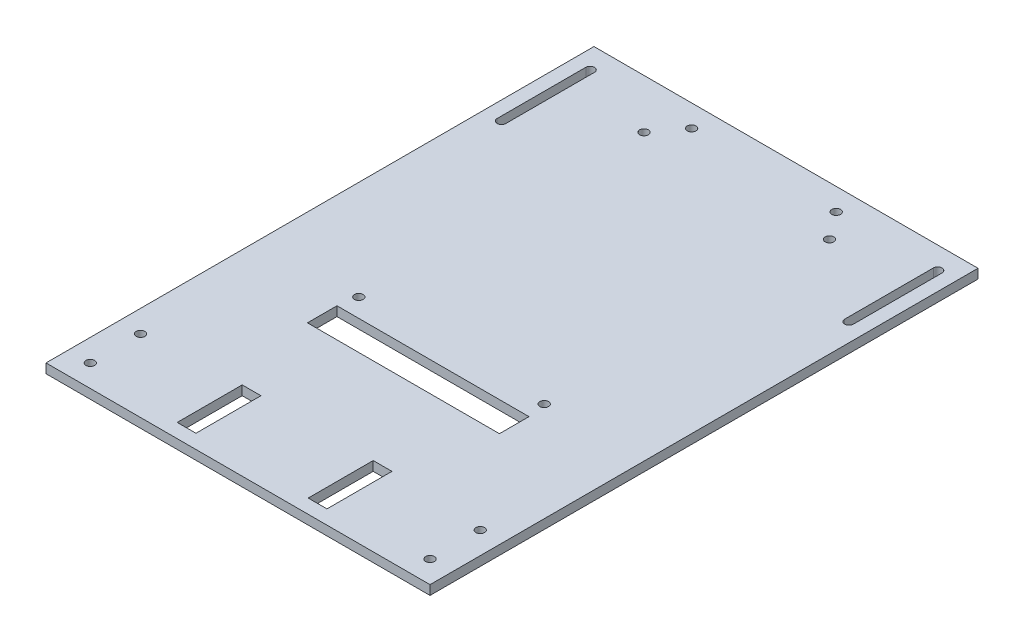
SolidWorks part; units mm, degrees
ref_plane "Front Plane" through (0, 0, 0) normal (0, 0, 1) x (1, 0, 0)
ref_plane "Top Plane" through (0, 0, 0) normal (0, 1, 0) x (1, 0, 0)
ref_plane "Right Plane" through (0, 0, 0) normal (1, 0, 0) x (0, 0, -1)
sketch "Sketch1" plane through (0, 0, 0) normal (0, 1, 0) x (1, 0, 0)
  line L1 (-65, -92.25) -> (65, -92.25)
  line L2 (-65, -92.25) -> (-65, 92.25)
  line L3 (-65, 92.25) -> (65, 92.25)
  line L4 (65, -92.25) -> (65, 92.25)
  line L5 (-65, -92.25) -> (65, 92.25) construction
  line L6 (-65, 92.25) -> (65, -92.25) construction
  point P0 (0, 0)
  dimension "D1" = 130
  dimension "D2" = 184.5
extrude "Boss-Extrude1" add sketch "Sketch1" along normal blind 3.175
sketch "Sketch4" plane through (0, 0, 0) normal (0, -1, 0) x (-1, 0, 0)
  line L6 (-58.825, 85.775) -> (-58.825, 55.775) construction
  line L7 (-57.35, 85.775) -> (-57.35, 55.775)
  line L8 (-60.3, 85.775) -> (-60.3, 55.775)
  line L36 (-65, -92.25) -> (-65, 92.25) construction
  line L46 (-65, 92.25) -> (65, 92.25) construction
  line L48 (58.825, 85.775) -> (58.825, 55.775) construction
  line L49 (60.3, 85.775) -> (60.3, 55.775)
  line L50 (57.35, 85.775) -> (57.35, 55.775)
  line L54 (65, 92.25) -> (65, -92.25) construction
  line L55 (65, -92.25) -> (-65, -92.25) construction
  arc A14 (-57.35, 85.775) -> (-60.3, 85.775) centre (-58.825, 85.775) ccw
  arc A15 (-60.3, 55.775) -> (-57.35, 55.775) centre (-58.825, 55.775) ccw
  circle A18 centre (-57.5, -84.75) radius 1.475
  circle A19 centre (-57.5, -67.75) radius 1.475
  arc A51 (60.3, 85.775) -> (57.35, 85.775) centre (58.825, 85.775) ccw
  arc A52 (57.35, 55.775) -> (60.3, 55.775) centre (58.825, 55.775) ccw
  circle A55 centre (57.5, -84.75) radius 1.475
  circle A56 centre (57.5, -67.75) radius 1.475
  point P2 (-58.825, 70.775)
  point P82 (58.825, 70.775)
  point P96 (-58.825, 87.25)
  point P100 (58.825, 87.25)
  dimension "D1" = 4.7
  dimension "D21" = 2.95
  dimension "D22" = 2.95
  dimension "D23" = 2.95
  dimension "D24" = 2.95
  dimension "D25" = 1.475
  dimension "D47" = 1.475
  dimension "D50" = 5
  dimension "D51" = 7.5
  dimension "D52" = 7.5
  dimension "D53" = 7.5
  dimension "D56" = 7.5
  dimension "D57" = 7.5
  dimension "D58" = 7.5
  dimension "D20" = 30
  dimension "D34" = 30
  dimension "D45" = 5
  dimension "D49" = 4.7
  dimension "D54" = 17
  dimension "D55" = 17
extrude "Cut-Extrude3" cut sketch "Sketch4" against normal through all
sketch "Sketch5" plane through (0, 0, 0) normal (0, -1, 0) x (1, 0, 0)
  line L0 (-23, -81.6775) -> (-23, -89.8725)
  line L1 (23, -91.5608) -> (23, -79.9892)
  line L3 (-28.3353, -87.25) -> (-20.6147, -87.25)
  line L4 (65, -92.25) -> (-65, -92.25) construction
  line L5 (65, -92.25) -> (-65, -92.25) construction
  circle A0 centre (-24.475, -85.775) radius 1.475
  circle A1 centre (24.475, -85.775) radius 1.475
  point P7 (-23.1414, -85.1449)
  point P10 (23, -85.775)
  point P16 (-24.475, -87.25)
  point P19 (-23, -85.775)
  point P21 (0, -92.25)
  dimension "D2" = 2.95
  dimension "D3" = 2.95
  dimension "D6" = 6.475
  dimension "D1" = 46
  dimension "D4" = 23
  dimension "D5" = 5
extrude "Cut-Extrude4" cut sketch "Sketch5" against normal blind 10 contours A0 | A1
sketch "Sketch6" plane through (0, 0, -92.25) normal (0, 0, -1) x (-1, 0, 0)
  line L1 (-65, 0) -> (65, 0)
  line L2 (-65, 0) -> (-65, 3.175)
  line L3 (-65, 3.175) -> (65, 3.175)
  line L4 (65, 0) -> (65, 3.175)
extrude "Boss-Extrude2" add sketch "Sketch6" along normal blind 1
sketch "Sketch7" plane through (0, 3.175, 0) normal (0, 1, 0) x (1, 0, 0)
  line L0 (-65, 93.25) -> (-65, -92.25) construction
  line L6 (-65, -92.25) -> (65, -92.25) construction
  line L7 (-25.35, -87.4884) -> (-19, -87.4884)
  line L8 (-25.35, -87.4884) -> (-25.35, -65.4884)
  line L9 (-25.35, -65.4884) -> (-19, -65.4884)
  line L10 (-19, -87.4884) -> (-19, -65.4884)
  line L11 (65, -92.25) -> (65, 93.25) construction
  line L12 (19, -87.4884) -> (25.35, -87.4884)
  line L13 (19, -87.4884) -> (19, -65.4884)
  line L14 (19, -65.4884) -> (25.35, -65.4884)
  line L15 (25.35, -87.4884) -> (25.35, -65.4884)
  dimension "D1" = 22
  dimension "D2" = 6.35
  dimension "D3" = 4.7616
  dimension "D4" = 39.65
  dimension "D5" = 6.35
  dimension "D6" = 22
  dimension "D7" = 4.7616
  dimension "D8" = 39.65
extrude "Cut-Extrude5" cut sketch "Sketch7" against normal through all both and the other way through all
sketch "Sketch8" plane through (0, 0, 0) normal (0, -1, 0) x (1, 0, 0)
  line L0 (-32.5, 92.25) -> (-32.5, 36.25)
  line L1 (-65, 92.25) -> (65, 92.25) construction
  line L3 (-32.5, 36.25) -> (32.5, 36.25)
  line L4 (-32.5, 36.25) -> (-32.5, 26.25)
  line L5 (-32.5, 26.25) -> (32.5, 26.25)
  line L6 (32.5, 36.25) -> (32.5, 26.25)
  line L7 (65, 92.25) -> (65, -93.25) construction
  dimension "D1" = 56
  dimension "D2" = 10
  dimension "D3" = 65
  dimension "D4" = 32.5
extrude "Cut-Extrude6" cut sketch "Sketch8" against normal blind 10 contours L6 L3 L4 L5
sketch "Sketch9" plane through (0, 0, 0) normal (0, -1, 0) x (-1, 0, 0)
  line L0 (-65, -92.25) -> (-65, 93.25) construction
  line L1 (30, 75.25) -> (-30, 75.25)
  line L2 (30, 75.25) -> (30, -12.75)
  line L3 (30, -12.75) -> (-30, -12.75)
  line L4 (-30, 75.25) -> (-30, -12.75)
  line L5 (30, 75.25) -> (-30, -12.75) construction
  line L6 (30, -12.75) -> (-30, 75.25) construction
  line L7 (-65, 93.25) -> (65, 93.25) construction
  circle A0 centre (30, -12.75) radius 1.475
  circle A1 centre (-30, -12.75) radius 1.475
  circle A2 centre (-30, 75.25) radius 1.475
  circle A3 centre (30, 75.25) radius 1.475
  point P0 (0, 31.25)
  dimension "D4" = 2.95
  dimension "D5" = 2.95
  dimension "D6" = 2.95
  dimension "D7" = 2.95
  dimension "D1" = 60
  dimension "D2" = 88
  dimension "D3" = 18
  dimension "D8" = 65
  dimension "D9" = 88
  dimension "D10" = 60
extrude "Cut-Extrude7" cut sketch "Sketch9" against normal blind 75 contours L4 A1 L3 | L1 A2 L4 | L4 A2 L1 | A0 | A3
sketch "Sketch10" plane through (0, 0, 0) normal (0, -1, 0) x (-1, 0, 0)
  line L1 (37.0787, -18.1638) -> (-41.0603, -18.1638)
  line L2 (37.0787, -18.1638) -> (37.0787, 79.6344)
  line L3 (37.0787, 79.6344) -> (-41.0603, 79.6344)
  line L4 (-41.0603, -18.1638) -> (-41.0603, 79.6344)
extrude "Boss-Extrude3" add sketch "Sketch10" against normal up to surface (3.175 mm away) up to face at (-30, 3.175, 11.275)
sketch "Sketch11" plane through (0, 0, 0) normal (0, -1, 0) x (-1, 0, 0)
  line L0 (-32.5, -36.25) -> (-32.5, -26.25) construction
  line L1 (32.5, -36.25) -> (32.5, -26.25) construction
  line L2 (32.5, -26.25) -> (-32.5, -26.25) construction
  circle A0 centre (31.39, -19.98) radius 1.475
  circle A1 centre (31.39, 76.57) radius 1.475
  circle A2 centre (-31.39, -19.98) radius 1.475
  circle A3 centre (-31.39, 76.57) radius 1.475
  dimension "D1" = 2.95
  dimension "D2" = 2.95
  dimension "D3" = 2.95
  dimension "D4" = 2.95
  dimension "D5" = 1.11
  dimension "D6" = 1.11
  dimension "D7" = 6.27
  dimension "D8" = 6.27
  dimension "D9" = 96.55
  dimension "D10" = 96.55
  dimension "D11" = 1.11
  dimension "D12" = 1.11
extrude "Cut-Extrude8" cut sketch "Sketch11" against normal blind 10
